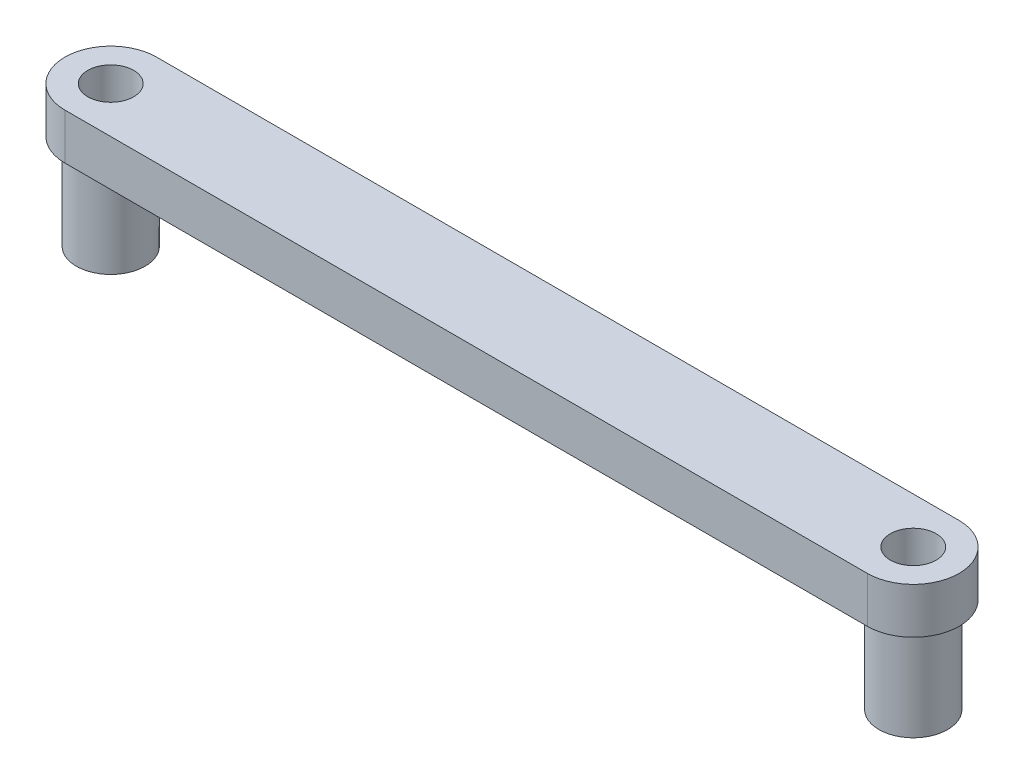
SolidWorks part; units mm, degrees
ref_plane "Front Plane" through (0, 0, 0) normal (0, 0, 1) x (1, 0, 0)
ref_plane "Top Plane" through (0, 0, 0) normal (0, 1, 0) x (1, 0, 0)
ref_plane "Right Plane" through (0, 0, 0) normal (1, 0, 0) x (0, 0, -1)
sketch "Sketch1" plane through (0, 0, 0) normal (0, 1, 0) x (1, 0, 0)
  circle A0 centre (0, 0) radius 1.5
  dimension "D1" = 3
extrude "Boss-Extrude1" add sketch "Sketch1" along normal blind 4.15
sketch "Sketch2" plane through (0, 4.15, 0) normal (0, 1, 0) x (1, 0, 0)
  line L0 (35, 0) -> (0, 0) construction
  line L1 (35, 2) -> (0, 2)
  line L2 (0, -2) -> (35, -2)
  line L3 (0, 2) -> (0, -2) construction
  arc A0 (0, 2) -> (0, -2) centre (0, 0) ccw
  arc A1 (35, -2) -> (35, 2) centre (35, 0) ccw
  dimension "D1" = 4
  dimension "D3" = 4
  dimension "D2" = 35
extrude "Boss-Extrude2" add sketch "Sketch2" along normal blind 2
sketch "Sketch3" plane through (0, 4.15, 0) normal (0, -1, 0) x (1, 0, 0)
  circle A0 centre (35, 0) radius 1.5
  dimension "D1" = 3
extrude "Boss-Extrude3" add sketch "Sketch3" along normal up to surface (4.15 mm away) up to face at (0, 0, 1.5)
sketch "Sketch4" plane through (0, 6.15, 0) normal (0, 1, 0) x (1, 0, 0)
  circle A0 centre (0, 0) radius 1
  circle A1 centre (35, 0) radius 1
  dimension "D1" = 2
extrude "Cut-Extrude1" cut sketch "Sketch4" against normal through all
